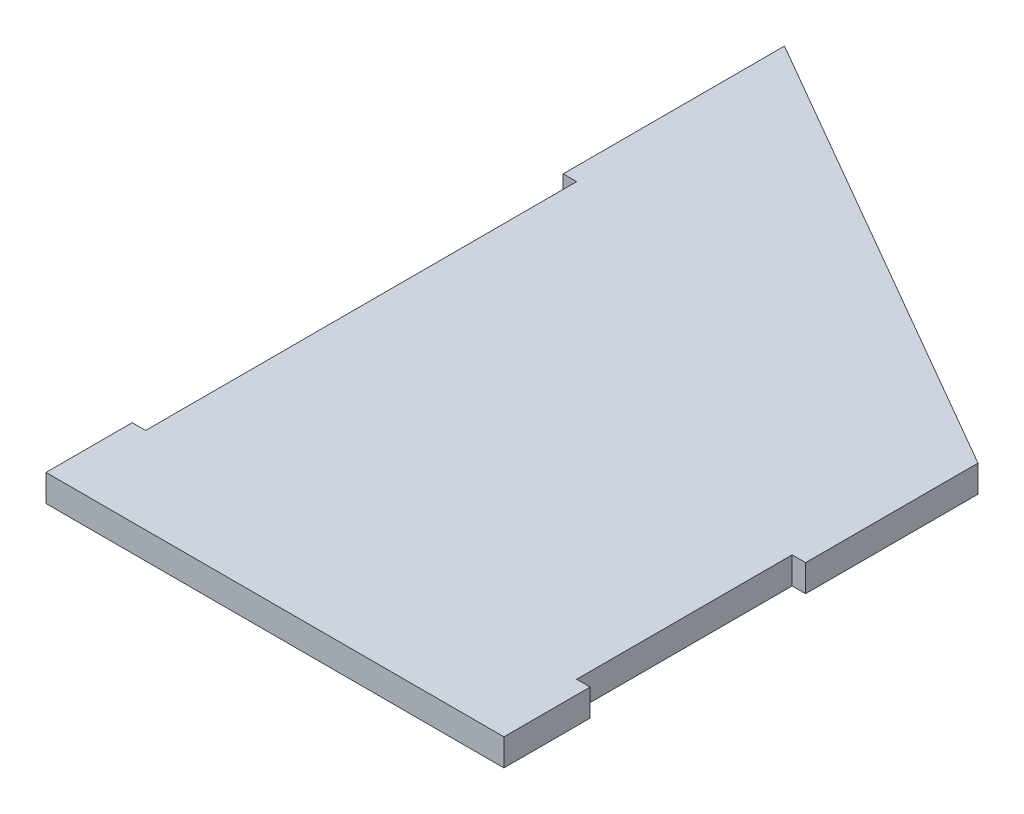
SolidWorks part; units mm, degrees
material "AISI 4130 Steel, annealed at 865C"
ref_plane "X-Y Datum" through (0, 0, 0) normal (0, 0, 1) x (1, 0, 0)
ref_plane "X-Z Datum" through (0, 0, 0) normal (0, 1, 0) x (1, 0, 0)
ref_plane "Y-Z Datum" through (0, 0, 0) normal (1, 0, 0) x (0, 0, -1)
sketch "Sketch1" plane through (0, 0, 0) normal (0, 1, 0) x (1, 0, 0)
  line L0 (-13.4937, -13.97) -> (-13.4937, -8.89) construction
  line L1 (-13.4937, -13.97) -> (13.4938, -13.97)
  line L2 (-13.4937, -13.97) -> (-13.4937, 13.97)
  line L3 (-13.4937, 13.97) -> (13.4938, 13.97)
  line L4 (13.4938, -13.97) -> (13.4938, 13.97)
  line L5 (-13.4937, -13.97) -> (13.4938, 13.97) construction
  line L6 (-13.4937, 13.97) -> (13.4938, -13.97) construction
  line L7 (0, -43.0151) -> (0, 43.0151) construction
  line L8 (-13.4937, -8.89) -> (-12.7, -8.89)
  line L9 (-13.4937, -8.89) -> (-13.4937, 16.51)
  line L10 (-13.4937, 16.51) -> (-12.7, 16.51)
  line L11 (-12.7, -8.89) -> (-12.7, 16.51)
  line L12 (13.4937, -8.89) -> (12.7, -8.89)
  line L13 (12.7, -8.89) -> (12.7, 3.81)
  line L14 (13.4937, 3.81) -> (12.7, 3.81)
  line L15 (-13.4937, 13.97) -> (-13.4937, 29.5512)
  line L16 (-13.4937, 29.5512) -> (13.4938, 13.97)
  point P1 (0, 0)
  dimension "D1" = 27.94
  dimension "D2" = 26.9875
  dimension "D3" = 5.08
  dimension "D4" = 0.7937
  dimension "D5" = 25.4
  dimension "D6" = 30
  dimension "D7" = 12.7
extrude "Boss-Extrude1" add sketch "Sketch1" along normal blind 1.5875 contours L14 L4 L3 L2 L10 L11 L8 L1 L12 L13 | L16 L15 L3
